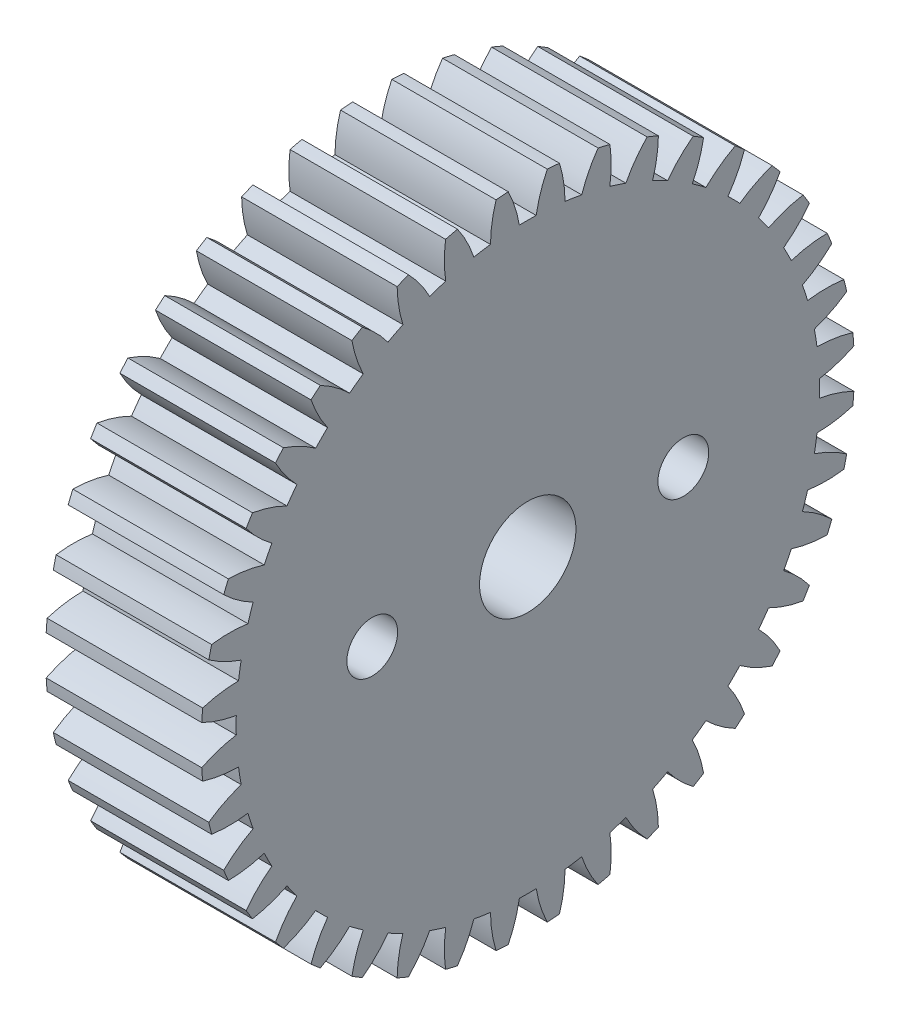
SolidWorks part; units mm, degrees
ref_plane "Plane1" through (0, 0, 0) normal (0, 0, 1) x (1, 0, 0)
ref_plane "Plane2" through (0, 0, 0) normal (0, 1, 0) x (1, 0, 0)
ref_plane "Plane3" through (0, 0, 0) normal (1, 0, 0) x (0, 0, -1)
sketch "HoldingSke" plane through (0, 0, 0) normal (0, 1, 0) x (1, 0, 0)
  line L0 (0, 0) -> (0.766, -0.6428)
  line L1 (-15, 0) -> (100, 0) construction
  line L2 (0, 0) -> (-2.1039, 2.3779)
  line L3 (0, 0) -> (-11.863, 4.5341)
  line L4 (0, 0) -> (6.6156, 5.5511)
  line L5 (0, 0) -> (-46.8476, -17.4728)
  line L6 (0, 0) -> (-8.2896, -5.593)
  line L7 (-2.1039, 2.3779) -> (8.6586, 51.2059)
  line L8 (-76.2, 54.61) -> (-75.2, 54.61)
  line L9 (-67.7845, 28.3722) -> (-49.3413, 33.142)
  line L10 (-76.2, 71.12) -> (104.1128, 71.12)
  line L11 (0, 0) -> (-10, 0)
  line L12 (-76.2, 101.6) -> (-76.162, 101.6)
  line L13 (24.9733, 27.94) -> (52.9518, 28.4284)
  line L14 (24.9733, 27.94) -> (24.9743, 27.94)
  line L15 (24.9733, 27.94) -> (100.4006, 29.5858)
  line L16 (-63.627, -1) -> (-12.827, -1)
  circle A0 centre (0, 0) radius 3
  circle A1 centre (0, 0) radius 18.749
  circle A2 centre (0, 0) radius 37.5
  circle A3 centre (0, 0) radius 3
  dimension "MHD" = 37.498
  dimension "Hub_dia" = 75
  dimension "Bore" = 6
  dimension "MBD" = 6
  dimension "Num_teeth" = 40
  dimension "Pitch" = 1
  dimension "Overall_len" = 50
  dimension "Show_teeth" = 40
  dimension "Thickness" = 10
  dimension "OAL" = 50.0001
  dimension "T_dim" = 1
  dimension "Ap" = 14.5
  dimension "H" = 19.05
  dimension "Pitch_radius" = 180.3128
  dimension "Width" = 10
  dimension "Backlash" = 0.038
  dimension "Addendum_fac" = 1
  dimension "Dedendum_fac" = 1.25
  dimension "Clearance_fac" = 0.25
  dimension "Dedendum_add" = 0.001
  dimension "Module" = 1
sketch "BasProSke" plane through (0, 0, 0) normal (0, 1, 0) x (1, 0, 0)
  line L0 (-10, 0) -> (60, 0) construction
  line L1 (0, 0) -> (0, 21)
  line L2 (0, 0) -> (10, 0)
  line L3 (10, 0) -> (10, 21)
  line L4 (10, 21) -> (0, 21)
  dimension "Thickness" = 10
  dimension "Diameter" = 42
revolve "Base-Revolve" add sketch "BasProSke" angle 360 about L0
sketch "TooCutSke" plane through (0, 0, 0) normal (1, 0, 0) x (0, 0, -1)
  line L1 (0, 0) -> (0, 107) construction
  line L2 (0, 0) -> (-0.8517, 19.9819) construction
  line L3 (0, 0) -> (-3.1363, 39.8509) construction
  line L4 (-0.8517, 19.9819) -> (-1.5682, 19.9255) construction
  arc A0 (0.5419, 18.7412) -> (-0.5419, 18.7412) centre (0, 0) ccw
  arc A1 (1.2681, 20.9871) -> (-1.2681, 20.9871) centre (0, 0) ccw
  circle A2 centre (0, 0) radius 20 construction
  circle A3 centre (0, 0) radius 19.363 construction
  arc A4 (-0.5419, 18.7412) -> (-1.2681, 20.9871) centre (-8.4337, 17.4298) ccw
  arc A5 (1.2681, 20.9871) -> (0.5419, 18.7412) centre (8.4337, 17.4298) ccw
  dimension "Root_dia" = 37.498
  dimension "Overcut_dia" = 42.0508
  dimension "Pitch_dia" = 40
  dimension "Base_dia" = 38.7259
  dimension "Flank_rad" = 8
  dimension "Half_ang" = 4.5
  dimension "Half_CT" = 0.7187
extrude "ToothCut" cut sketch "TooCutSke" along normal through all
fillet "Breaks" [suppressed] radius 0.02
fillet "RootFillets" [suppressed] radius 0.251
pattern_circular "TeethCuts" count 40 every 9 about axis through (-10, 0, 0) along (1, 0, 0) of "ToothCut", "RootFillets", "Breaks"
sketch "HubNeaOneSke" plane through (0, 0, 0) normal (-1, 0, 0) x (0, 0, 1)
  circle A0 centre (0, 0) radius 18.749
  dimension "Diameter" = 37.498
extrude "HubNearOne" [suppressed] add sketch "HubNeaOneSke" along normal blind 40.0001
sketch "HubNeaBotSke" plane through (0, 0, 0) normal (-1, 0, 0) x (0, 0, 1)
  circle A0 centre (0, 0) radius 18.749
  dimension "Diameter" = 37.498
extrude "HubNearBoth" [suppressed] add sketch "HubNeaBotSke" along normal blind 20
ref_plane "FarPln" through (10, 0, 0) normal (1, 0, 0) x (0, 0, -1)
sketch "HubFarSke" plane through (10, 0, 0) normal (1, 0, 0) x (0, 0, -1)
  circle A0 centre (0, 0) radius 18.749
  dimension "Diameter" = 37.498
extrude "HubFar" [suppressed] add sketch "HubFarSke" along normal blind 20
sketch "BorSke" plane through (0, 0, 0) normal (1, 0, 0) x (0, 0, -1)
  circle A0 centre (0, 0) radius 3
  dimension "Diameter" = 6
extrude "Bore" cut sketch "BorSke" along normal mid plane 100.0001
sketch "KeySke" plane through (0, 0, 0) normal (1, 0, 0) x (0, 0, -1)
  line L0 (-1, 0) -> (-1, 4)
  line L1 (-1, 4) -> (1, 4)
  line L2 (1, 4) -> (1, 0)
  line L3 (0, 0) -> (0, 34) construction
  line L4 (-1, 0) -> (1, 0)
  dimension "Offset" = 4
  dimension "Width" = 2
extrude "Keyway" [suppressed] cut sketch "KeySke" along normal mid plane 100.0001
pattern_circular "Keyway2" [suppressed] count 2 every 90 about axis through (-10, 0, 0) along (1, 0, 0)
hole_wizard "#4 Clearance Hole1" positions "Sketch1" profile "Sketch2" hole size "#4" standard "ANSI Inch" end condition through all
sketch "Sketch1" plane through (10, 0, 0) normal (1, 0, 0) x (0, 0, -1)
  circle A0 centre (0, 0) radius 3 construction
  point P0 (-10, 0)
  point P2 (10, 0)
  dimension "D1" = 10
  dimension "D2" = 10
  dimension "D3" = 0
sketch "Sketch2" plane through (10, 0, 10) normal (0, 1, 0) x (0, 0, -1)
  line L0 (0, 0) -> (0, 10)
  line L1 (0, 10) -> (1.6319, 10)
  line L2 (1.6319, 10) -> (1.632, 0)
  line L5 (1.632, 0) -> (0, 0)
  line L11 (0, -6.35) -> (0, 107.95) construction
  dimension "Thru Hole Dia." = 3.2639
  dimension "Thru Hole Depth" = 10
sketch "Sketch3" plane through (10, 0, 0) normal (1, 0, 0) x (0, 0, -1)
  circle A0 centre (0, 0) radius 3.1
  dimension "D1" = 6.2
extrude "Cut-Extrude1" cut sketch "Sketch3" against normal through all
equation "' \"Module@HoldingSke\" = 6.35"
equation "' \"Num_teeth@HoldingSke\" = 12"
equation "' \"Ap@HoldingSke\" =  20"
equation "' \"Ap@HoldingSke\" = 20"
equation "' \"Width@HoldingSke\" = 0.5 * 25.4"
equation "' \"Hub_dia@HoldingSke\"= 1 * 25.4"
equation "' \"Hub_dia@HoldingSke\" = 1 * 25.4"
equation "' \"Overall_len@HoldingSke\" = 1.0 * 25.4"
equation "' \"Bore@HoldingSke\" = 0.75 * 25.4"
equation "' \"T_dim@HoldingSke\" = 0.1 * 25.4"
equation "' \"Width@KeySke\" = 0.25 * 25.4"
equation "' \"Show_teeth@HoldingSke\" = 13"
equation "' \"Backlash@HoldingSke\" = 0.009 * 25.4"
equation "' \"Addendum_fac@HoldingSke\" = 1.0"
equation "' \"Dedendum_fac@HoldingSke\" = 1.25"
equation "' \"Dedendum_add@HoldingSke\" = 0.00005 * 25.4"
equation "' \"Clearance_fac@HoldingSke\" = 0.25"
equation "\"Pitch@HoldingSke\" = 1 / \"Module@HoldingSke\""
equation "\"Overcut_dia@TooCutSke\" = (\"Num_teeth@HoldingSke\" + 2 * \"Addendum_fac@HoldingSke\") / \"Pitch@HoldingSke\" + 0.002 * 25.4"
equation "\"Pitch_dia@TooCutSke\" = \"Num_teeth@HoldingSke\" / \"Pitch@HoldingSke\""
equation "\"Base_dia@TooCutSke\" = \"Num_teeth@HoldingSke\" / \"Pitch@HoldingSke\" * cos((\"Ap@HoldingSke\"  * 3.14159265 / 180))"
equation "\"Root_dia@TooCutSke\" = (\"Num_teeth@HoldingSke\" + 2) / \"Pitch@HoldingSke\" - 2 * (\"Addendum_fac@HoldingSke\" + \"Dedendum_fac@HoldingSke\") / \"Pitch@HoldingSke\" - \"Dedendum_add@HoldingSke\" * 2"
equation "\"Half_ang@TooCutSke\" = 180 / \"Num_teeth@HoldingSke\""
equation "\"Half_CT@TooCutSke\" = \"Num_teeth@HoldingSke\" / \"Pitch@HoldingSke\" * sin((3.14159265 / 2 / \"Num_teeth@HoldingSke\")) / 2 - 7 * \"Backlash@HoldingSke\" / 4"
equation "\"Flank_rad@TooCutSke\" = \"Num_teeth@HoldingSke\" / \"Pitch@HoldingSke\" / 5"
equation "\"Radius@RootFillets\" = \"Clearance_fac@HoldingSke\" / \"Pitch@HoldingSke\" + \"Dedendum_add@HoldingSke\""
equation "\"Break_rad@Breaks\" = 0.02 / \"Pitch@HoldingSke\""
equation "\"Thickness@HoldingSke\" = \"Width@HoldingSke\""
equation "\"OAL@HoldingSke\" = \"Thickness@HoldingSke\""
equation "\"MHD@HoldingSke\" = (\"Num_teeth@HoldingSke\" + 2) / \"Pitch@HoldingSke\" - 2 * (\"Addendum_fac@HoldingSke\" + \"Dedendum_fac@HoldingSke\")  / \"Pitch@HoldingSke\" - \"Dedendum_add@HoldingSke\" * 2"
equation "\"MBD@HoldingSke\" = (\"Num_teeth@HoldingSke\" + 2) / \"Pitch@HoldingSke\" - 2 * (\"Addendum_fac@HoldingSke\" + \"Dedendum_fac@HoldingSke\")  / \"Pitch@HoldingSke\" - \"Dedendum_add@HoldingSke\" * 2 - 0.002 * 25.4"
equation "\"MHD@HoldingSke\" = ((sgn( \"MHD@HoldingSke\" - \"Hub_dia@HoldingSke\" )-1)*( \"MHD@HoldingSke\" - \"Hub_dia@HoldingSke\" ))/-2+ \"Hub_dia@HoldingSke\""
equation "\"MBD@HoldingSke\" = ((sgn( \"MBD@HoldingSke\" - \"Bore@HoldingSke\" )-1)*( \"MBD@HoldingSke\" - \"Bore@HoldingSke\" ))/-2+ \"Bore@HoldingSke\""
equation "\"OAL@HoldingSke\" = ((sgn( \"OAL@HoldingSke\" - \"Overall_len@HoldingSke\" )+1)*( \"OAL@HoldingSke\" - \"Overall_len@HoldingSke\" ))/2 + \"Overall_len@HoldingSke\" + 0.000002 * 25.4"
equation "\"Num_teeth@TeethCuts\" = int( \"Show_teeth@HoldingSke\" ) + 1"
equation "\"Num_teeth@TeethCuts\" = ((sgn( \"Num_teeth@TeethCuts\" - \"Num_teeth@HoldingSke\" )-1)*( \"Num_teeth@TeethCuts\" - \"Num_teeth@HoldingSke\" ))/-2+ \"Num_teeth@HoldingSke\""
equation "\"Num_teeth@TeethCuts\" = ((sgn( \"Num_teeth@TeethCuts\" - 2.0)+1)*( \"Num_teeth@TeethCuts\" - 2.0))/2 +2.0"
equation "\"Angle@TeethCuts\" = 360.0 / \"Num_teeth@HoldingSke\""
equation "\"Diameter@BasProSke\" = (\"Num_teeth@HoldingSke\" + 2 * \"Addendum_fac@HoldingSke\") / \"Pitch@HoldingSke\""
equation "\"Thickness@BasProSke\"  = \"Thickness@HoldingSke\""
equation "' \"Fillet_rad@BasProSke\" =  \"Thickness@HoldingSke\" * 0.05"
equation "' \"Fillet_rad@BasProSke\" = \"Thickness@HoldingSke\" * 0.05"
equation "\"MHD@HoldingSke\" = ((sgn( \"MHD@HoldingSke\" - \"Root_dia@TooCutSke\" )-1)*( \"MHD@HoldingSke\" - \"Root_dia@TooCutSke\" ))/-2+ \"Root_dia@TooCutSke\""
equation "\"Diameter@HubNeaOneSke\" = \"MHD@HoldingSke\""
equation "\"Length@HubNearOne\" = \"OAL@HoldingSke\" - \"Thickness@BasProSke\""
equation "\"Diameter@HubNeaBotSke\" = \"MHD@HoldingSke\""
equation "\"Length@HubNearBoth\" = ( \"OAL@HoldingSke\" - \"Thickness@BasProSke\" ) / 2.0"
equation "\"Thickness@FarPln\" = \"Thickness@BasProSke\""
equation "\"Diameter@HubFarSke\" = \"MHD@HoldingSke\""
equation "\"Length@HubFar\" = ( \"OAL@HoldingSke\" - \"Thickness@BasProSke\" ) / 2.0"
equation "\"Diameter@BorSke\" = \"MBD@HoldingSke\""
equation "\"D1@Bore\" = \"OAL@HoldingSke\" * 2.0"
equation "\"D1@Keyway\" = \"OAL@HoldingSke\" * 2.0"
equation "\"Offset@KeySke\" = \"T_dim@HoldingSke\" + \"MBD@HoldingSke\" / 2.0"
